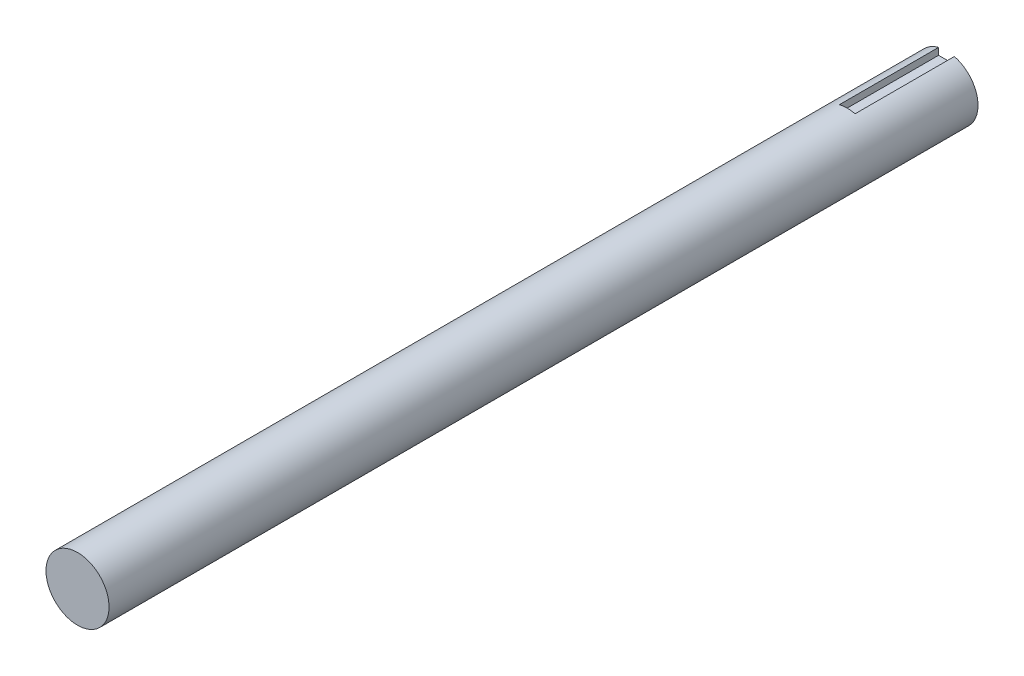
SolidWorks part; units mm, degrees
ref_plane "Alzado" through (0, 0, 0) normal (0, 0, 1) x (1, 0, 0)
ref_plane "Planta" through (0, 0, 0) normal (0, 1, 0) x (1, 0, 0)
ref_plane "Vista lateral" through (0, 0, 0) normal (1, 0, 0) x (0, 0, -1)
sketch "Croquis1" plane through (0, 0, 0) normal (0, 0, 1) x (1, 0, 0)
  line L1 (-12.7, -12.7) -> (12.7, -12.7)
  line L2 (-12.7, -12.7) -> (-12.7, 12.7)
  line L3 (-12.7, 12.7) -> (12.7, 12.7)
  line L4 (12.7, -12.7) -> (12.7, 12.7)
  line L5 (-12.7, -12.7) -> (12.7, 12.7) construction
  line L6 (-12.7, 12.7) -> (12.7, -12.7) construction
  point P0 (0, 0)
  dimension "D1" = 25.4
  dimension "D2" = 25.4
extrude "Saliente-Extruir1" add sketch "Croquis1" along normal mid plane 320
sketch "Croquis3" plane through (0, 0, 160) normal (0, 0, 1) x (1, 0, 0)
  circle A0 centre (0, 0) radius 12.7
  circle A1 centre (0, 0) radius 19.21
extrude "Cortar-Extruir1" cut sketch "Croquis3" against normal blind 5
sketch "Croquis4" plane through (0, 0, -160) normal (0, 0, -1) x (-1, 0, 0)
  circle A0 centre (0, 0) radius 12.7
  circle A1 centre (0, 0) radius 26.3352
extrude "Cortar-Extruir2" cut sketch "Croquis4" against normal blind 5
sketch "Croquis6" plane through (0, 0, -160) normal (0, 0, -1) x (-1, 0, 0)
  circle A0 centre (0, 0) radius 12.7
extrude "Saliente-Extruir3" add sketch "Croquis6" along normal blind 30
sketch "Croquis7" plane through (0, 0, -190) normal (0, 0, -1) x (-1, 0, 0)
  line L1 (3.175, 15.875) -> (-3.175, 15.875)
  line L2 (3.175, 15.875) -> (3.175, 9.525)
  line L3 (3.175, 9.525) -> (-3.175, 9.525)
  line L4 (-3.175, 15.875) -> (-3.175, 9.525)
  line L5 (3.175, 15.875) -> (-3.175, 9.525) construction
  line L6 (3.175, 9.525) -> (-3.175, 15.875) construction
  circle A0 centre (0, 0) radius 12.7 construction
  point P0 (0, 12.7)
  dimension "D1" = 6.35
  dimension "D2" = 6.35
extrude "Cortar-Extruir5" cut sketch "Croquis7" against normal blind 40
sketch "Croquis8" plane through (0, 0, -190) normal (0, 0, -1) x (-1, 0, 0)
  circle A0 centre (0, 0) radius 12.7
  circle A1 centre (0, 0) radius 28.2195
extrude "Cortar-Extruir6" cut sketch "Croquis8" against normal blind 359
